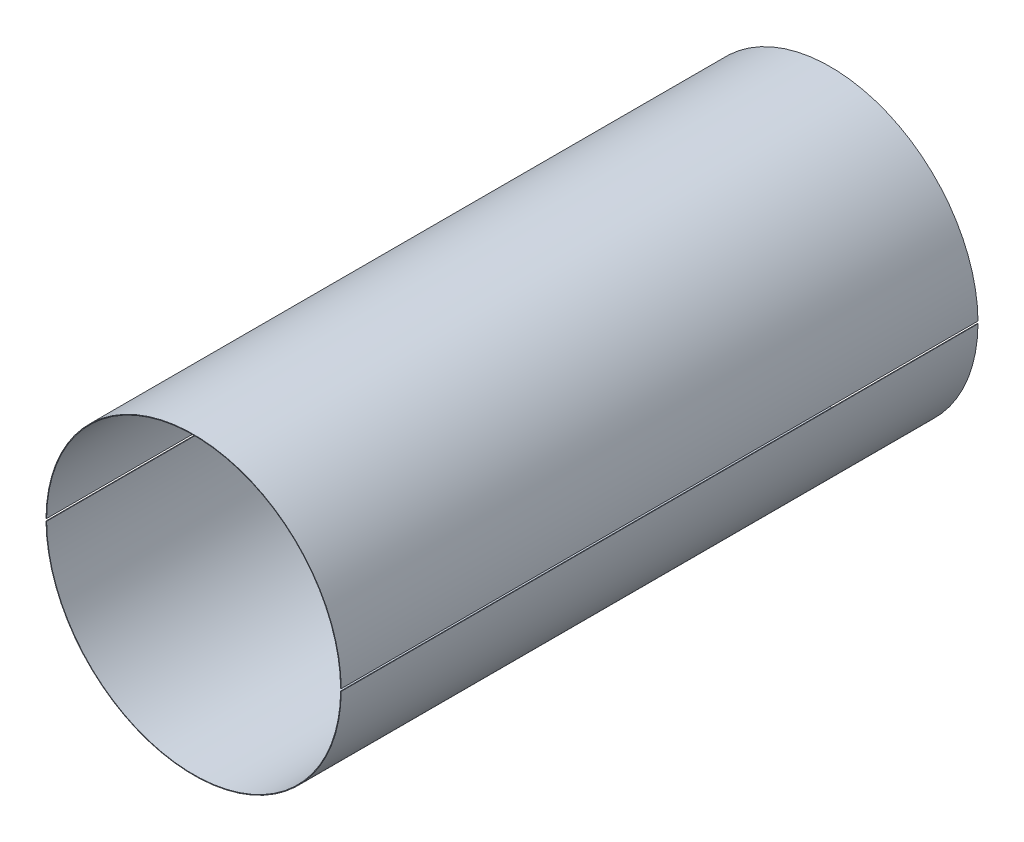
SolidWorks part; units mm, degrees
ref_plane "Front" through (0, 0, 0) normal (0, 0, 1) x (1, 0, 0)
ref_plane "Top" through (0, 0, 0) normal (0, 1, 0) x (1, 0, 0)
ref_plane "Right" through (0, 0, 0) normal (1, 0, 0) x (0, 0, -1)
sketch "Sketch2" plane through (0, 0, 0) normal (0, 0, 1) x (1, 0, 0)
  circle A0 centre (0, 0) radius 64.77
  circle A1 centre (0, 0) radius 64.516
  dimension "D1" = 129.54
  dimension "D2" = 129.032
extrude "Boss-Extrude1" add sketch "Sketch2" along normal blind 279.4
sketch "Sketch3" plane through (0, 0, 279.4) normal (0, 0, 1) x (1, 0, 0)
  line L0 (-71.4518, 0) -> (70.1682, 0) construction
  line L1 (0, 68.3498) -> (0, -67.2802) construction
ref_plane "Plane1" through (-64.77, 0, 0) normal (-1, 0, 0) x (0, 0, 1)
sketch "Sketch5" plane through (-64.77, 0, 0) normal (-1, 0, 0) x (0, 0, 1)
  line L0 (-8.3863, 0) -> (289.133, 0) construction
  line L1 (0, 0.508) -> (279.4, 0.508)
  line L2 (0, 64.77) -> (0, -64.77) construction
  line L3 (279.4, 68.3498) -> (279.4, -67.2802) construction
  line L4 (279.4, 0.508) -> (279.4, -0.508)
  line L5 (0, 0.508) -> (0, -0.508)
  line L6 (0, -0.508) -> (279.4, -0.508)
  point P12 (279.4, 0)
  point P13 (0, 0)
  dimension "D1" = 0.508
extrude "Cut-Extrude1" cut sketch "Sketch5" against normal through all both and the other way through all
